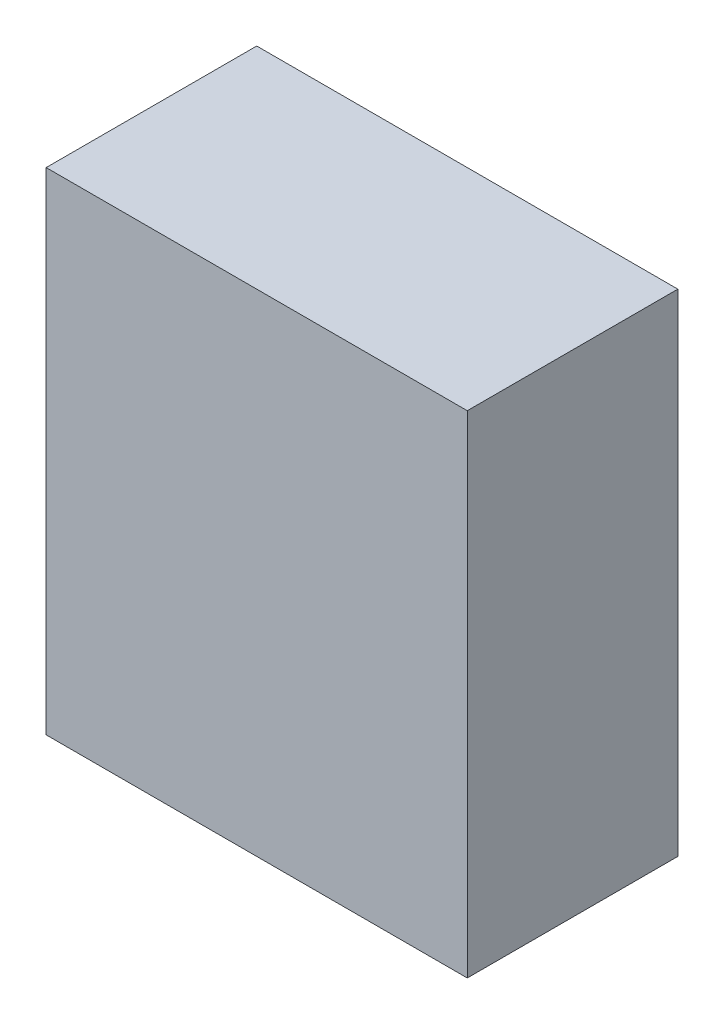
SolidWorks part; units mm, degrees
ref_plane "前基準面" through (0, 0, 0) normal (0, 0, 1) x (1, 0, 0)
ref_plane "上基準面" through (0, 0, 0) normal (0, 1, 0) x (1, 0, 0)
ref_plane "右基準面" through (0, 0, 0) normal (1, 0, 0) x (0, 0, -1)
sketch "草圖1" plane through (0, 0, 0) normal (0, 0, 1) x (1, 0, 0)
  line L1 (-54.6519, 3.6385) -> (5.3481, 3.6385)
  line L2 (-54.6519, 3.6385) -> (-54.6519, -66.3615)
  line L3 (-54.6519, -66.3615) -> (5.3481, -66.3615)
  line L4 (5.3481, 3.6385) -> (5.3481, -66.3615)
  dimension "D1" = 70
  dimension "D2" = 60
extrude "填料-伸長2" add sketch "草圖1" along normal blind 30
